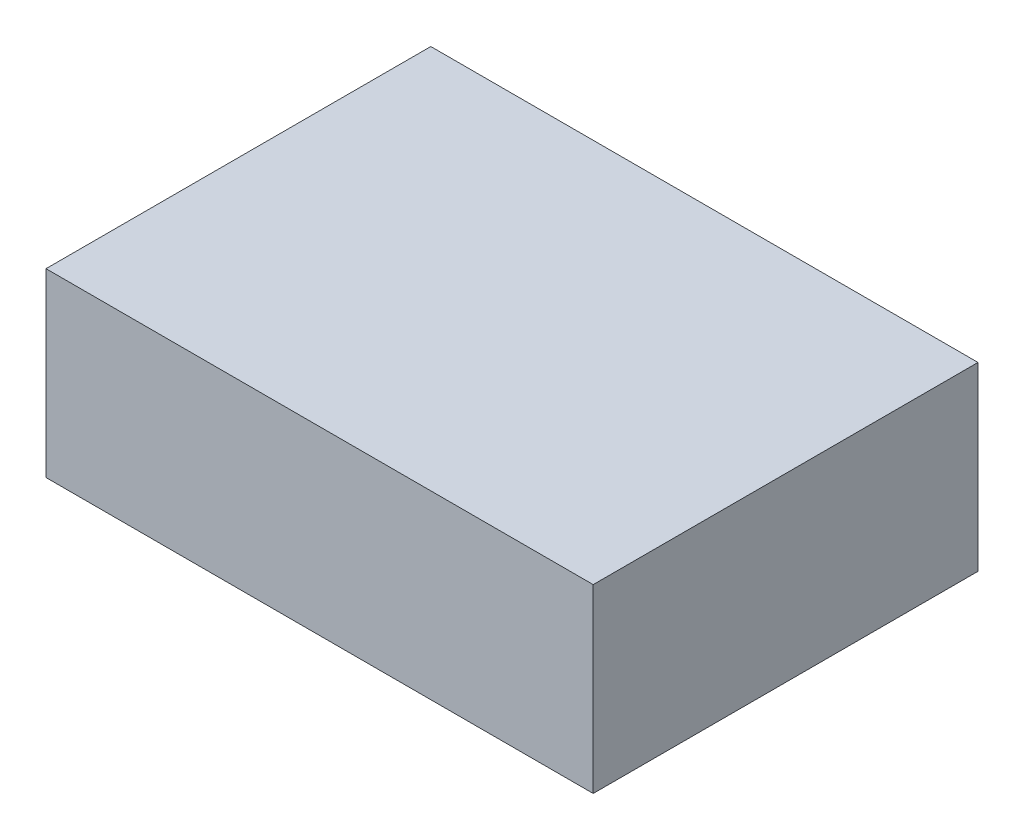
SolidWorks part; units mm, degrees
ref_plane "Front Plane" through (0, 0, 0) normal (0, 0, 1) x (1, 0, 0)
ref_plane "Top Plane" through (0, 0, 0) normal (0, 1, 0) x (1, 0, 0)
ref_plane "Right Plane" through (0, 0, 0) normal (1, 0, 0) x (0, 0, -1)
sketch "Sketch1" plane through (0, 0, 0) normal (0, 1, 0) x (1, 0, 0)
  line L1 (-54.75, -38.5) -> (54.75, -38.5)
  line L2 (-54.75, -38.5) -> (-54.75, 38.5)
  line L3 (-54.75, 38.5) -> (54.75, 38.5)
  line L4 (54.75, -38.5) -> (54.75, 38.5)
  line L5 (-54.75, -38.5) -> (54.75, 38.5) construction
  line L6 (-54.75, 38.5) -> (54.75, -38.5) construction
  point P0 (0, 0)
  dimension "D1" = 77
  dimension "D2" = 109.5
extrude "Boss-Extrude1" add sketch "Sketch1" along normal blind 36.2
